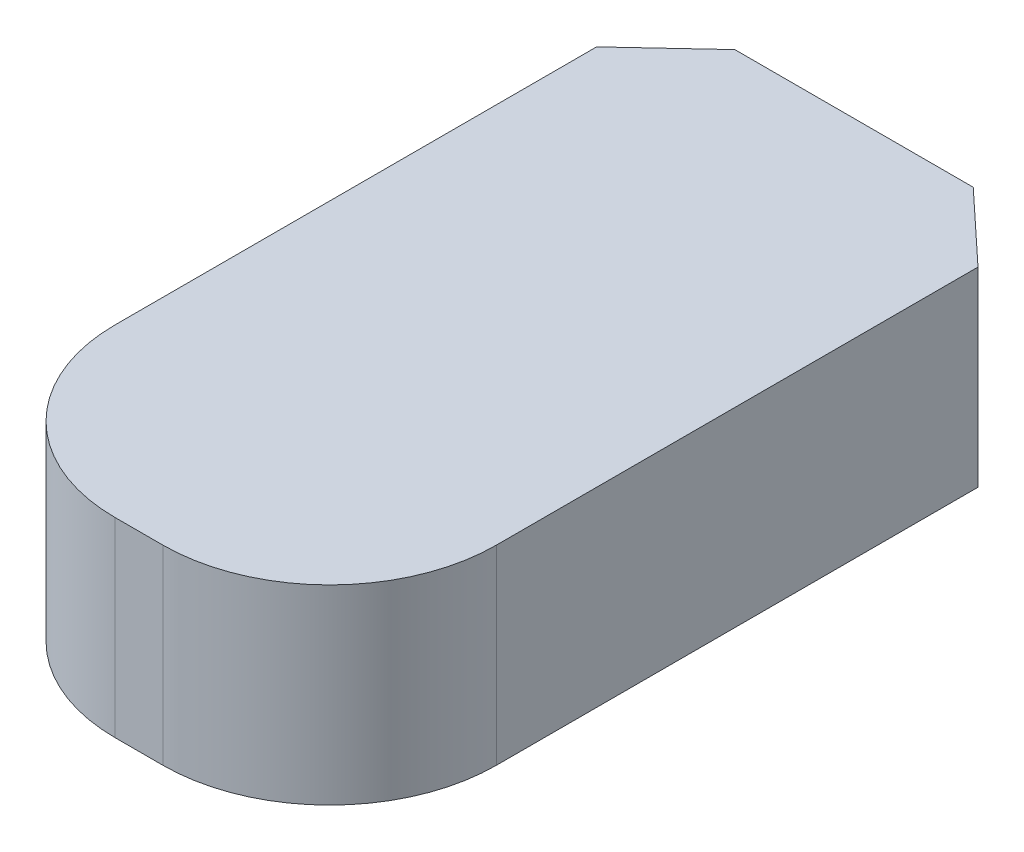
SolidWorks part; units mm, degrees
ref_plane "Front Plane" through (0, 0, 0) normal (0, 0, 1) x (1, 0, 0)
ref_plane "Top Plane" through (0, 0, 0) normal (0, 1, 0) x (1, 0, 0)
ref_plane "Right Plane" through (0, 0, 0) normal (1, 0, 0) x (0, 0, -1)
sketch "Sketch1" plane through (0, 0, 0) normal (0, 1, 0) x (1, 0, 0)
  line L1 (-12.5, 37.5) -> (12.5, 37.5)
  line L2 (-20, 30.5) -> (-20, -20)
  line L3 (-2.5, -37.5) -> (2.5, -37.5)
  line L4 (20, 30.5) -> (20, -20)
  line L5 (-17.5074, 32.8264) -> (20, -37.5) construction
  line L6 (-20, -37.5) -> (17.5074, 32.8264) construction
  line L10 (-12.5, 37.5) -> (-20, 30.5)
  line L11 (12.5, 37.5) -> (20, 30.5)
  arc A0 (2.5, -37.5) -> (20, -20) centre (2.5, -20) ccw
  arc A1 (-20, -20) -> (-2.5, -37.5) centre (-2.5, -20) ccw
  point P0 (0, 0)
  point P4 (0, 37.5)
  dimension "D3" = 17.5
  dimension "D1" = 25
  dimension "D2" = 40
  dimension "D4" = 75
  dimension "D6" = 7
  dimension "D7" = 7
extrude "Boss-Extrude2" add sketch "Sketch1" along normal blind 20
sketch "Sketch2" plane through (0, 20, 0) normal (0, 1, 0) x (1, 0, 0)
  line L0 (0, 37.5) -> (0, 2.5) construction
  line L3 (12.5, 37.5) -> (12.5, 15)
  line L5 (-12.5, 37.5) -> (12.5, 37.5)
  line L6 (-12.5, 37.5) -> (-12.5, 15)
  line L8 (0, 2.5) -> (0, 15) construction
  line L9 (0, 37.5) -> (0, 17.5) construction
  arc A2 (-12.5, 15) -> (12.5, 15) centre (0, 15) ccw
  circle A3 centre (0, 17.5) radius 10
  dimension "D2" = 12.5
  dimension "D4" = 20
  dimension "D1" = 35
  dimension "D3" = 20
